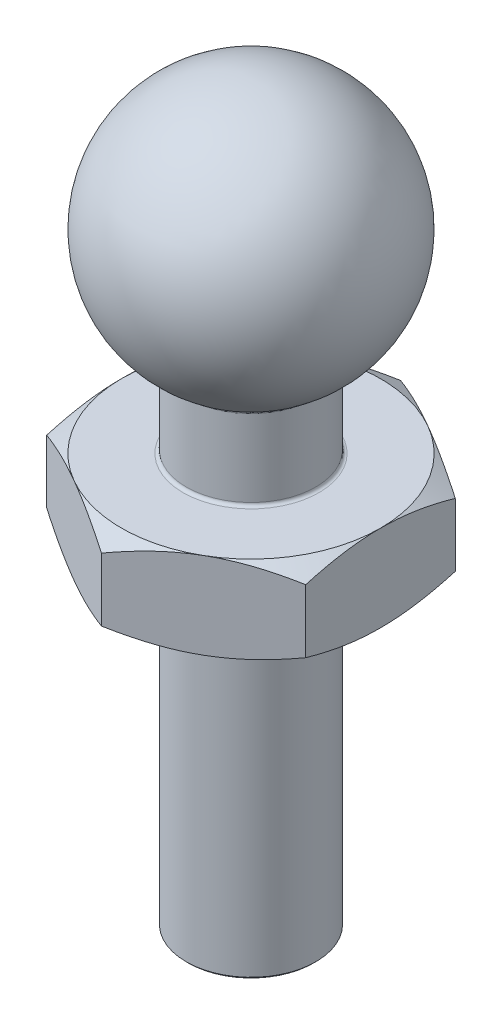
SolidWorks part; units mm, degrees
ref_plane "Front Plane" through (0, 0, 0) normal (0, 0, 1) x (1, 0, 0)
ref_plane "Top Plane" through (0, 0, 0) normal (0, 1, 0) x (1, 0, 0)
ref_plane "Right Plane" through (0, 0, 0) normal (1, 0, 0) x (0, 0, -1)
sketch "Sketch1" plane through (0, 0, 0) normal (0, 0, 1) x (1, 0, 0)
  line L1 (0, 0) -> (1.5, 0)
  line L2 (1.5, 0) -> (1.5, 11.4019)
  line L3 (0, 17) -> (0, 11)
  line L4 (0, 11) -> (0, 0)
  circle A0 centre (0, 14) radius 3 construction
  arc A1 (0, 17) -> (1.5, 11.4019) centre (0, 14) cw
  point P9 (0, 0)
  dimension "D1" = 6
  dimension "D2" = 1.5
  dimension "D3" = 11
revolve "Revolve1" add sketch "Sketch1" angle 360 about L4
sketch "Sketch2" plane through (0, 0, 0) normal (0, 0, 1) x (1, 0, 0)
  line L0 (-4.1251, 7.5) -> (4.1251, 7.5)
  point P2 (0, 7.5)
  dimension "D1" = 7.5
split line "Split Line1"
chamfer "Chamfer1" distance 0.05 angle 45 1 edges at (0, 0, 1.5)
ref_plane "Plane1" through (0, 7.5, 0) normal (0, 1, 0) x (1, 0, 0)
sketch "Sketch3" plane through (0, 7.5, 0) normal (0, 1, 0) x (1, 0, 0)
  line L1 (0, -3.4641) -> (3, -1.7321)
  line L2 (3, -1.7321) -> (3, 1.7321)
  line L3 (3, 1.7321) -> (0, 3.4641)
  line L4 (0, 3.4641) -> (-3, 1.7321)
  line L5 (-3, 1.7321) -> (-3, -1.7321)
  line L6 (-3, -1.7321) -> (0, -3.4641)
  circle A0 centre (0, 0) radius 1.5
  circle A1 centre (0, 0) radius 3 construction
  circle A2 centre (0, 0) radius 1.5 construction
  point P3 (0, 0)
  dimension "D1" = 6
extrude "Boss-Extrude1" add sketch "Sketch3" along normal blind 2
sketch "Sketch4" plane through (0, 7.5, 0) normal (0, -1, 0) x (1, 0, 0)
  circle A0 centre (0, 0) radius 3 construction
  circle A1 centre (0, 0) radius 3
extrude "Cut-Extrude1" cut sketch "Sketch4" against normal blind 2 draft 60 flip side to cut
sketch "Sketch5" plane through (0, 9.5, 0) normal (0, 1, 0) x (1, 0, 0)
  circle A1 centre (0, 0) radius 3
  circle A2 centre (0, 0) radius 3
  dimension "D1" = 0
extrude "Cut-Extrude2" cut sketch "Sketch5" against normal blind 2 draft 60 flip side to cut
fillet "Fillet1" radius 0.075 2 edges at (0, 11.4019, 1.5) (0, 9.5, 1.5)
